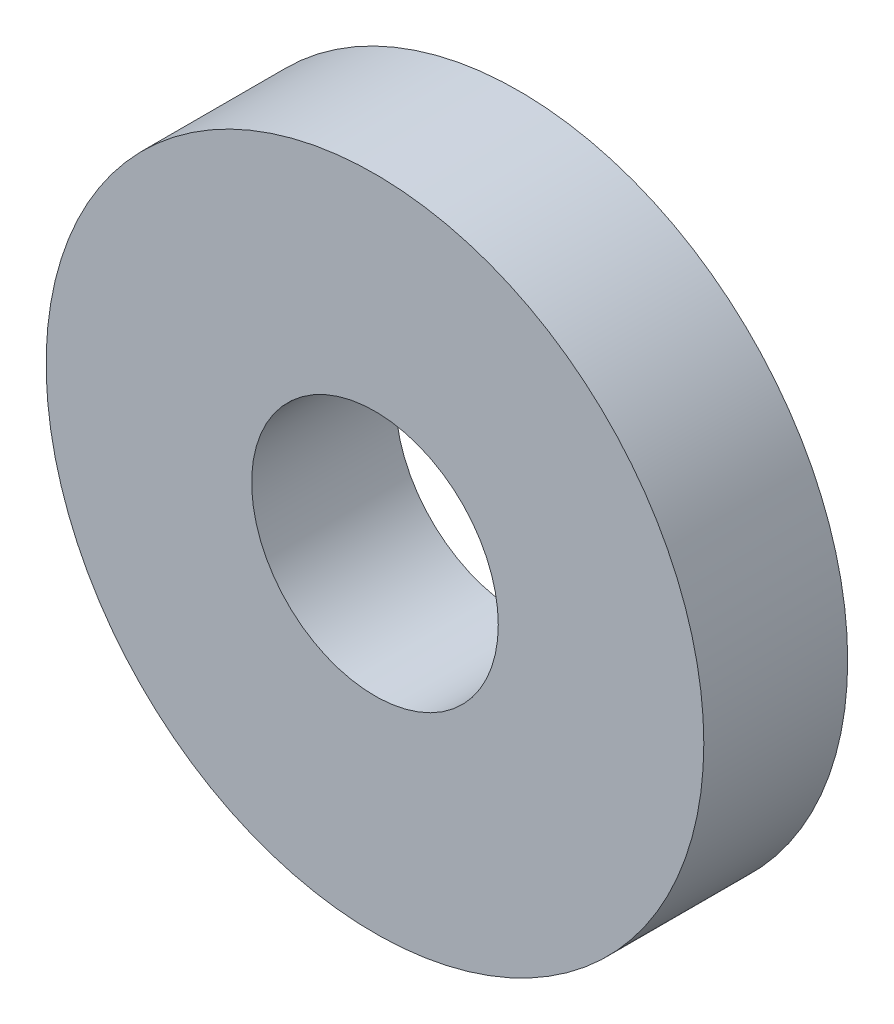
SolidWorks part; units mm, degrees
material "NBR"
ref_plane "Front Plane" through (0, 0, 0) normal (0, 0, 1) x (1, 0, 0)
ref_plane "Top Plane" through (0, 0, 0) normal (0, 1, 0) x (1, 0, 0)
ref_plane "Right Plane" through (0, 0, 0) normal (1, 0, 0) x (0, 0, -1)
sketch "Sketch1" plane through (0, 0, 0) normal (0, 1, 0) x (1, 0, 0)
  line L0 (6, -47) -> (16, -47)
  line L1 (16, -47) -> (16, -54)
  line L2 (16, -54) -> (6, -54)
  line L3 (6, -54) -> (6, -47)
  line L4 (0, -150) -> (0, 150) construction
revolve "REV_Radial_Seal_12x32x7_envelope" add sketch "Sketch1" angle 360 about L4
